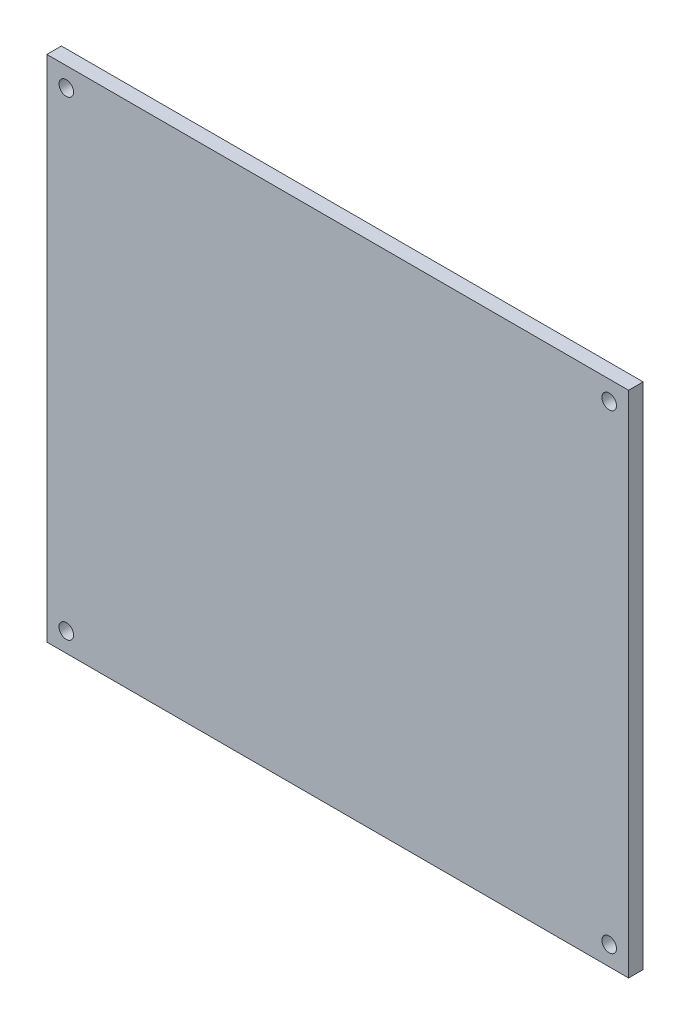
SolidWorks part; units mm, degrees
ref_plane "前视基准面" through (0, 0, 0) normal (0, 0, 1) x (1, 0, 0)
ref_plane "上视基准面" through (0, 0, 0) normal (0, 1, 0) x (1, 0, 0)
ref_plane "右视基准面" through (0, 0, 0) normal (1, 0, 0) x (0, 0, -1)
other "Configuration Table"
sketch "草图1" plane through (0, 0, 0) normal (0, 0, 1) x (1, 0, 0)
  line L1 (-60, 52.5) -> (60, 52.5)
  line L2 (-60, 52.5) -> (-60, -52.5)
  line L3 (-60, -52.5) -> (60, -52.5)
  line L4 (60, 52.5) -> (60, -52.5)
  line L5 (0, -52.5) -> (0, 52.5) construction
  line L6 (-60, 0) -> (60, 0) construction
  point P0 (0, 0)
  dimension "D1" = 120
  dimension "D2" = 105
extrude "凸台-拉伸1" add sketch "草图1" along normal blind 3
sketch "草图2" plane through (0, 0, 3) normal (0, 0, 1) x (1, 0, 0)
  line L0 (60, 52.5) -> (-60, 52.5) construction
  line L1 (-56, 48.5) -> (56, 48.5) construction
  line L2 (-56, 48.5) -> (-56, -48.5) construction
  line L3 (-56, -48.5) -> (56, -48.5) construction
  line L4 (56, 48.5) -> (56, -48.5) construction
  line L5 (0, -48.5) -> (0, 48.5) construction
  line L6 (-56, 0) -> (56, 0) construction
  line L7 (60, -52.5) -> (60, 52.5) construction
  circle A0 centre (-56, 48.5) radius 1.5
  circle A1 centre (56, 48.5) radius 1.5
  circle A2 centre (56, -48.5) radius 1.5
  circle A3 centre (-56, -48.5) radius 1.5
  point P0 (0, 0)
  dimension "D3" = 3
  dimension "D1" = 4
  dimension "D2" = 4
extrude "切除-拉伸1" cut sketch "草图2" against normal blind 10
